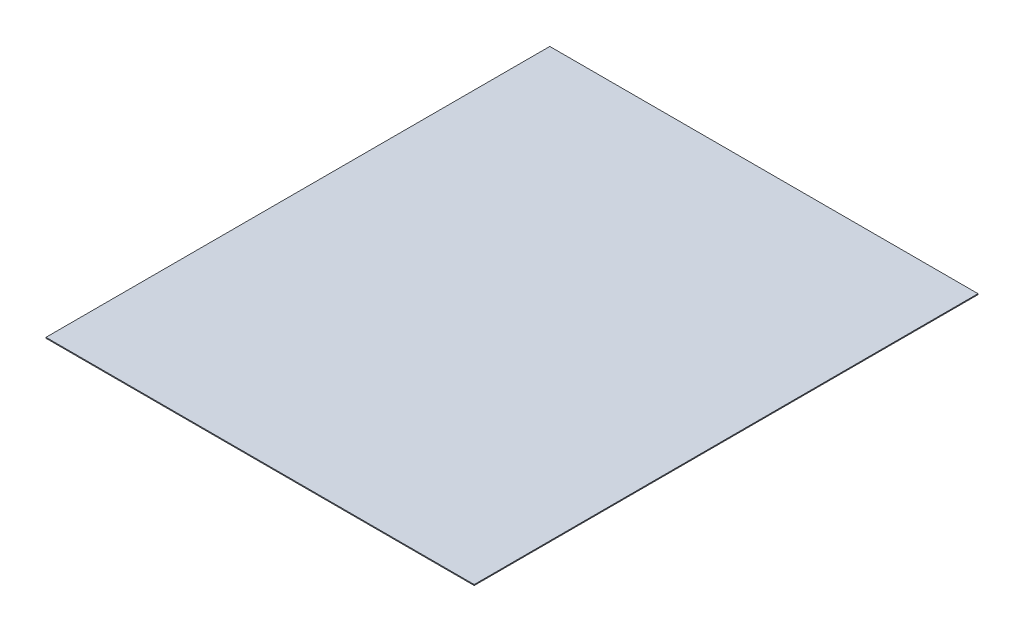
SolidWorks part; units mm, degrees
ref_plane "Front Plane" through (0, 0, 0) normal (0, 0, 1) x (1, 0, 0)
ref_plane "Top Plane" through (0, 0, 0) normal (0, 1, 0) x (1, 0, 0)
ref_plane "Right Plane" through (0, 0, 0) normal (1, 0, 0) x (0, 0, -1)
other "Configuration Table"
sketch "Sketch1" plane through (0, 0, 0) normal (0, 0, 1) x (1, 0, 0)
  line L1 (1.5, 1968.5) -> (698.5, 1968.5)
  line L2 (1.5, 1968.5) -> (1.5, 1970)
  line L3 (1.5, 1970) -> (698.5, 1970)
  line L4 (698.5, 1968.5) -> (698.5, 1970)
extrude "PRESS_dis_ust_1" add sketch "Sketch1" against normal blind 820 separate body
